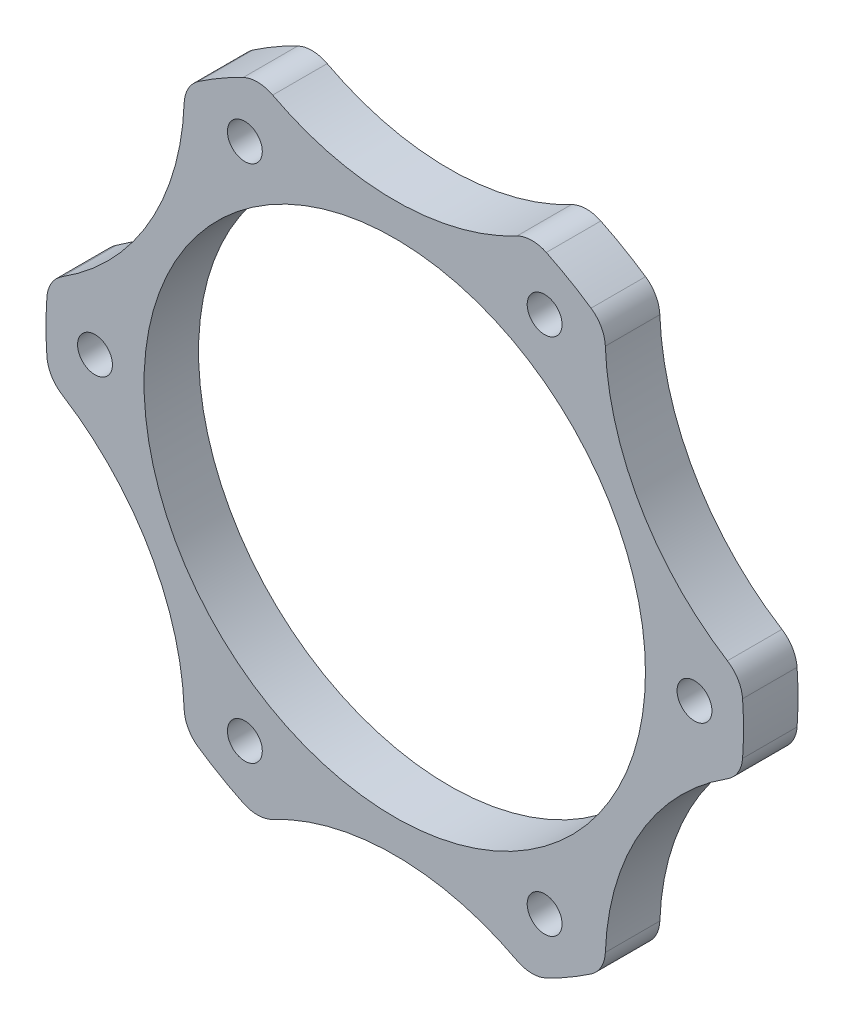
SolidWorks part; units mm, degrees
material "Thornel Mat VMA"
ref_plane "前视基准面" through (0, 0, 0) normal (0, 0, 1) x (1, 0, 0)
ref_plane "上视基准面" through (0, 0, 0) normal (0, 1, 0) x (1, 0, 0)
ref_plane "右视基准面" through (0, 0, 0) normal (1, 0, 0) x (0, 0, -1)
sketch "草图1" plane through (0, 0, 0) normal (0, 0, 1) x (1, 0, 0)
  circle A0 centre (0, 0) radius 32
  circle A1 centre (0, 0) radius 23
  dimension "D1" = 64
  dimension "D2" = 46
extrude "凸台-拉伸1" add sketch "草图1" along normal blind 5
sketch "草图2" plane through (0, 0, 5) normal (0, 0, 1) x (1, 0, 0)
  circle A0 centre (0, 0) radius 50 construction
  circle A1 centre (0, 50) radius 24
  dimension "D1" = 100
  dimension "D2" = 48
extrude "切除-拉伸1" cut sketch "草图2" against normal blind 10
pattern_circular "阵列(圆周)1" count 6 over 360 about axis through (0, 0, 0) along (0, 0, 1) of "切除-拉伸1"
sketch "草图3" plane through (0, 0, 5) normal (0, 0, 1) x (1, 0, 0)
  line L0 (0, 27.5) -> (0, 0) construction
  line L1 (0, 0) -> (27.5, 0) construction
  line L2 (0, 0) -> (13.75, 23.8157) construction
  circle A0 centre (0, 0) radius 27.5 construction
  circle A1 centre (13.75, 23.8157) radius 1.6
  dimension "D1" = 55
  dimension "D3" = 3.2
  dimension "D2" = 60
extrude "切除-拉伸2" cut sketch "草图3" against normal blind 10
pattern_circular "阵列(圆周)2" count 6 over 360 about axis through (0, 0, 0) along (0, 0, 1) of "切除-拉伸2"
fillet "圆角1" radius 3 12 edges at (19.3069, 25.5195, 2.5) (31.754, 3.9605, 2.5) (-12.4471, 29.48, 2.5) (12.4471, 29.48, 2.5) (-31.754, 3.9605, 2.5) (-19.3069, 25.5195, 2.5) (-19.3069, -25.5195, 2.5) (-31.754, -3.9605, 2.5) (12.4471, -29.48, 2.5) (-12.4471, -29.48, 2.5) (31.754, -3.9605, 2.5) (19.3069, -25.5195, 2.5)
